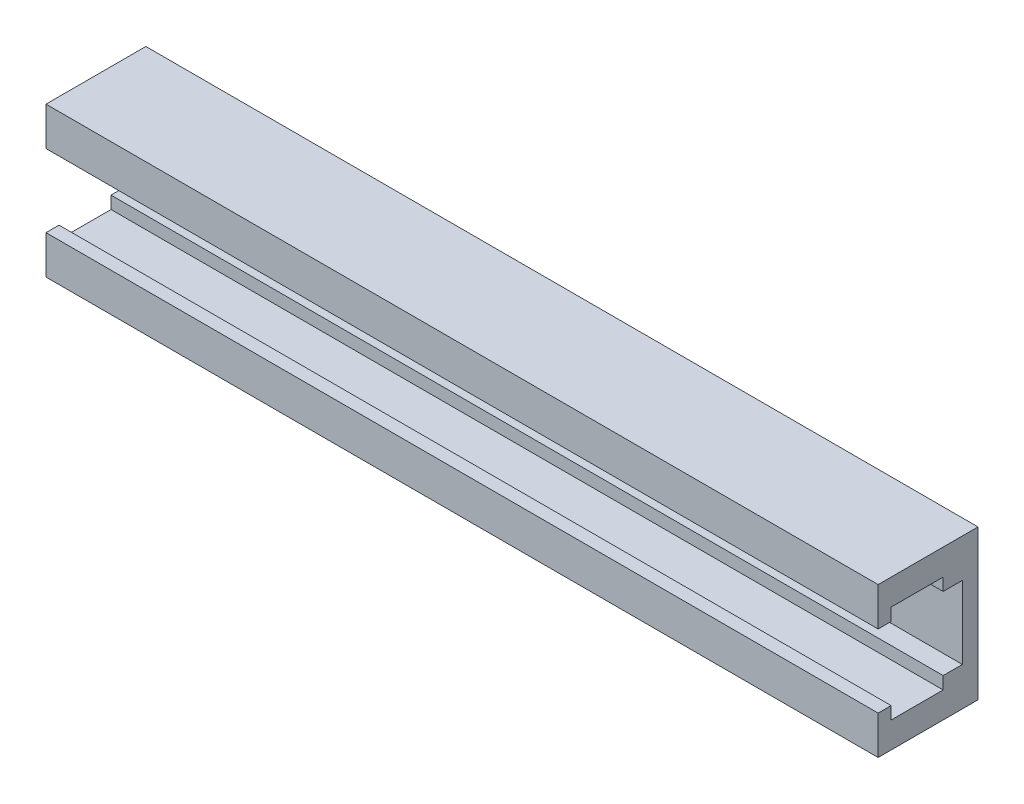
SolidWorks part; units mm, degrees
ref_plane "Front" through (0, 0, 0) normal (0, 0, 1) x (1, 0, 0)
ref_plane "Top" through (0, 0, 0) normal (0, 1, 0) x (1, 0, 0)
ref_plane "Right" through (0, 0, 0) normal (1, 0, 0) x (0, 0, -1)
sketch "Sketch1" plane through (0, 0, 0) normal (1, 0, 0) x (0, 0, -1)
  line L1 (0, 9.144) -> (-12.192, 9.144)
  line L2 (0, 9.144) -> (0, -9.144)
  line L3 (0, -9.144) -> (-12.192, -9.144)
  line L4 (-12.192, 9.144) -> (-12.192, -9.144)
  point P4 (0, 0)
  dimension "D1" = 18.288
  dimension "D2" = 12.192
sketch "Sketch2" plane through (0, 0, 0) normal (1, 0, 0) x (0, 0, -1)
  line L0 (0, 9.144) -> (-12.192, 9.144)
  line L1 (-12.192, 9.144) -> (-12.192, 4.445)
  line L2 (-12.192, 9.144) -> (-12.192, -9.144) construction
  line L3 (-12.192, 4.445) -> (-10.6045, 4.445)
  line L4 (-10.6045, 4.445) -> (-10.6045, 5.969)
  line L5 (-10.6045, 5.969) -> (-4.2545, 5.969)
  line L6 (-4.2545, 5.969) -> (-4.2545, 4.445)
  line L7 (-4.2545, 4.445) -> (-1.905, 4.445)
  line L8 (-1.905, 4.445) -> (-1.905, -4.445)
  line L9 (-1.905, -4.445) -> (-4.2545, -4.445)
  line L10 (-4.2545, -4.445) -> (-4.2545, -5.969)
  line L11 (-4.2545, -5.969) -> (-10.6045, -5.969)
  line L12 (-10.6045, -5.969) -> (-10.6045, -4.445)
  line L13 (-10.6045, -4.445) -> (-12.192, -4.445)
  line L14 (-12.192, -4.445) -> (-12.192, -9.144)
  line L15 (-12.192, -9.144) -> (0, -9.144)
  line L16 (0, -9.144) -> (0, 9.144)
  line L17 (0, 0) -> (-19.0377, 0) construction
  point P25 (-1.905, 0)
  dimension "D1" = 1.905
  dimension "D2" = 8.89
  dimension "D3" = 3.175
  dimension "D4" = 6.35
  dimension "D5" = 8.89
  dimension "D6" = 1.5875
extrude "Boss-Extrude1" add sketch "Sketch2" along normal mid plane 101.6
sketch "Sketch3" plane through (0, 0, 1.905) normal (0, 0, 1) x (1, 0, 0)
  line L0 (0, 0) -> (38.1, 0) construction
  line L1 (0, 0) -> (0, 27.0833) construction
  circle A0 centre (38.1, 0) radius 2.413
  dimension "D2" = 4.826
  dimension "D1" = 76.2
extrude "Cut-Extrude1" cut sketch "Sketch3" against normal up to surface (1.905 mm away) up to face at (0, 0, 0)
pattern_linear "LPattern1" count 3 spacing 76.2 along (-1, 0, 0) of "Cut-Extrude1"
other "SurfaceCut1"
mirror "Mirror1" about plane through (0, 0, 0) normal (1, 0, 0) of bodies 112
